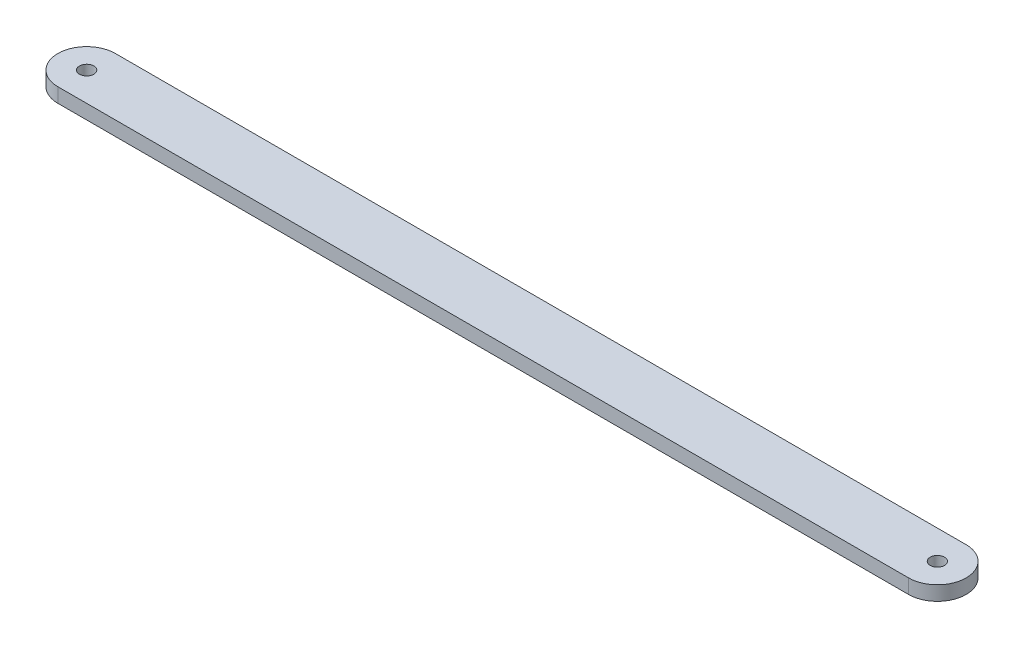
SolidWorks part; units mm, degrees
ref_plane "前基準面" through (0, 0, 0) normal (0, 0, 1) x (1, 0, 0)
ref_plane "上基準面" through (0, 0, 0) normal (0, 1, 0) x (1, 0, 0)
ref_plane "右基準面" through (0, 0, 0) normal (1, 0, 0) x (0, 0, -1)
sketch "草圖1" plane through (0, 0, 0) normal (0, 1, 0) x (1, 0, 0)
  line L0 (-147.85, 0) -> (147.85, 0) construction
  line L1 (-147.85, 10) -> (147.85, 10)
  line L2 (-147.85, -10) -> (147.85, -10)
  arc A0 (-147.85, 10) -> (-147.85, -10) centre (-147.85, 0) ccw
  arc A1 (147.85, -10) -> (147.85, 10) centre (147.85, 0) ccw
  circle A2 centre (-147.85, 0) radius 2.5
  circle A3 centre (147.85, 0) radius 2.5
  point P3 (0, 0)
  dimension "D2" = 10
  dimension "D3" = 5
  dimension "D1" = 295.7
extrude "填料-伸長1" add sketch "草圖1" along normal blind 5
